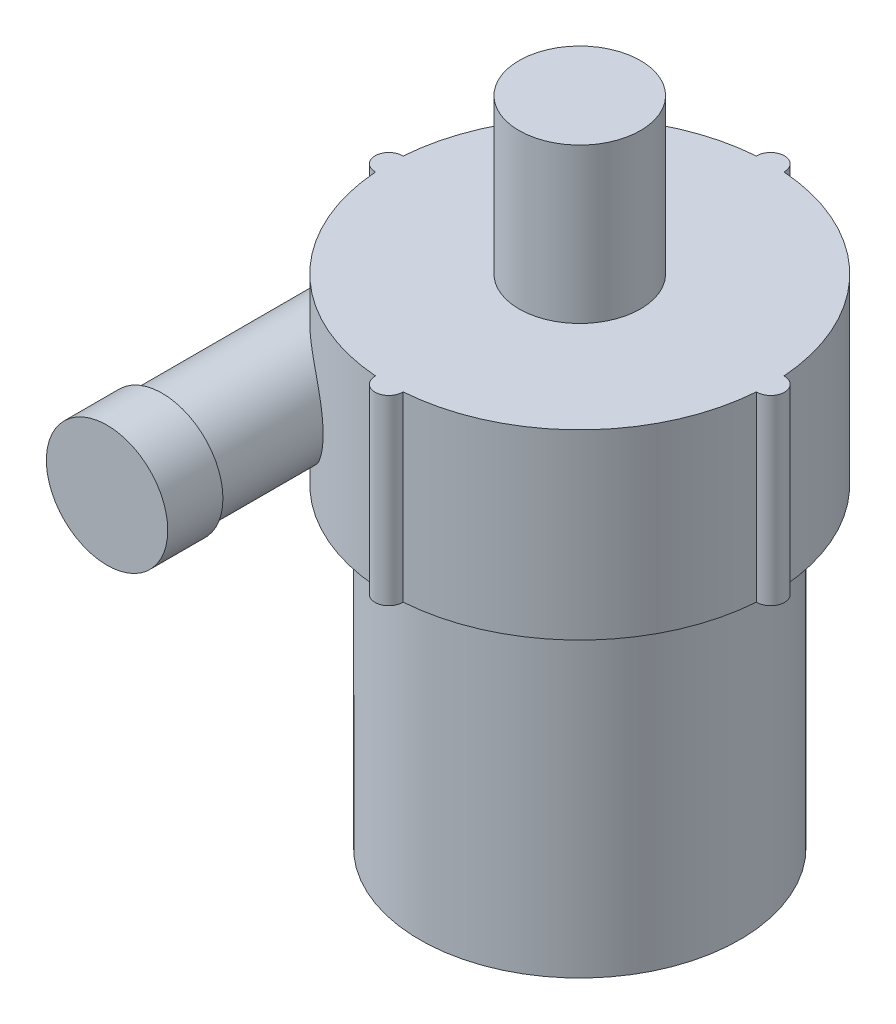
SolidWorks part; units mm, degrees
ref_plane "Front Plane" through (0, 0, 0) normal (0, 0, 1) x (1, 0, 0)
ref_plane "Top Plane" through (0, 0, 0) normal (0, 1, 0) x (1, 0, 0)
ref_plane "Right Plane" through (0, 0, 0) normal (1, 0, 0) x (0, 0, -1)
sketch "Sketch1" plane through (0, 0, 0) normal (0, 1, 0) x (1, 0, 0)
  circle A0 centre (0, 0) radius 29
  dimension "D1" = 58
extrude "Boss-Extrude1" add sketch "Sketch1" along normal blind 90
sketch "Sketch2" plane through (0, 90, 0) normal (0, 1, 0) x (1, 0, 0)
  circle A0 centre (0, 0) radius 11
  dimension "D1" = 22
extrude "Boss-Extrude2" add sketch "Sketch2" along normal blind 28
sketch "Sketch3" plane through (0, 90, 0) normal (0, 1, 0) x (1, 0, 0)
  circle A0 centre (0, 0) radius 34.6
  dimension "D1" = 69.2
extrude "Boss-Extrude3" add sketch "Sketch3" against normal blind 33
sketch "Sketch4" plane through (0, 90, 0) normal (0, 1, 0) x (1, 0, 0)
  circle A0 centre (0, 34.6) radius 2.5
  circle A1 centre (0, 0) radius 34.6 construction
  circle A2 centre (-34.6, 0) radius 2.5
  circle A3 centre (0, -34.6) radius 2.5
  circle A4 centre (34.6, 0) radius 2.5
  point P16 (0, 0)
  dimension "D1" = 5
  dimension "D2" = 4
extrude "Boss-Extrude4" add sketch "Sketch4" against normal blind 33
sketch "Sketch5" plane through (0, 0, 0) normal (0, 0, 1) x (1, 0, 0)
  circle A0 centre (-25.6651, 72.4467) radius 10
  dimension "D1" = 20
extrude "Boss-Extrude5" add sketch "Sketch5" along normal blind 60 contours A0
sketch "Sketch6" plane through (0, 0, 60) normal (0, 0, 1) x (1, 0, 0)
  circle A0 centre (-25.6651, 72.4467) radius 11
  dimension "D1" = 22
extrude "Boss-Extrude6" add sketch "Sketch6" against normal blind 10
